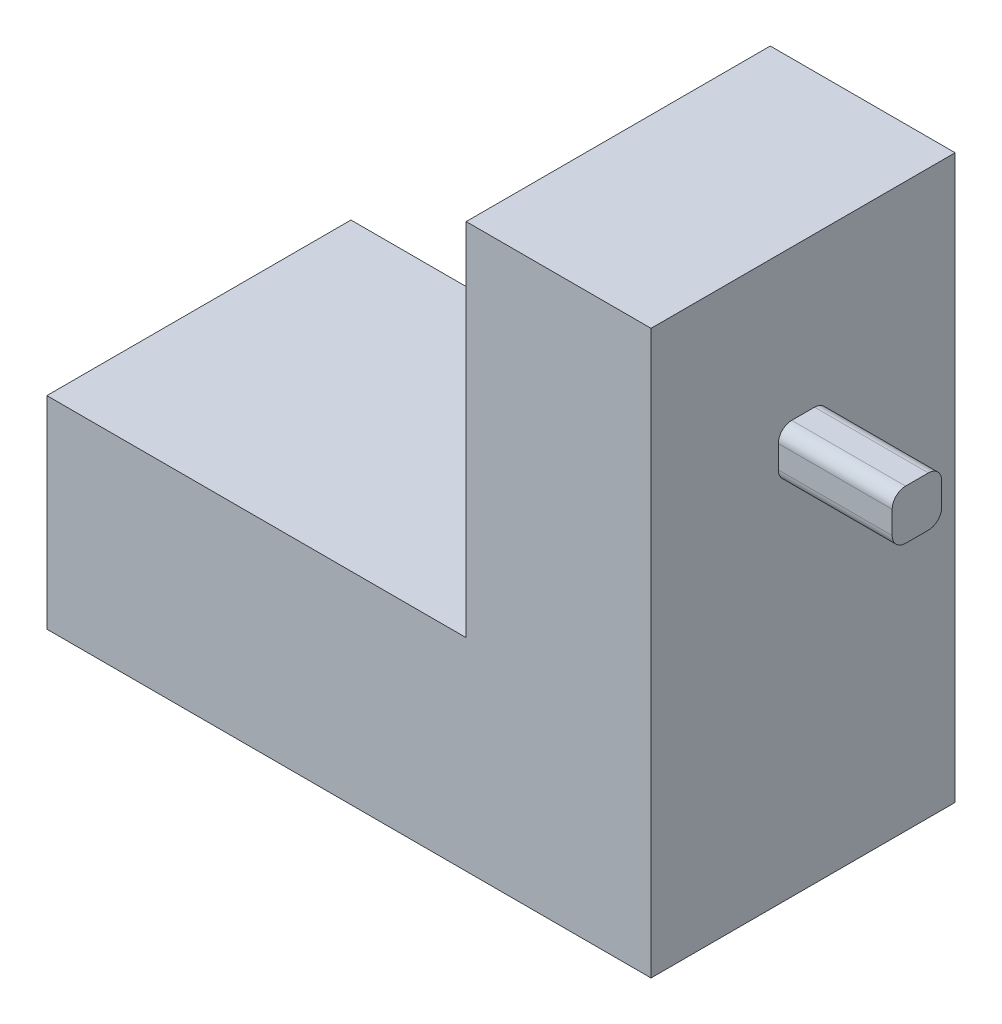
SolidWorks part; units mm, degrees
ref_plane "Plano frontal" through (0, 0, 0) normal (0, 0, 1) x (1, 0, 0)
ref_plane "Plano superior" through (0, 0, 0) normal (0, 1, 0) x (1, 0, 0)
ref_plane "Plano direito" through (0, 0, 0) normal (1, 0, 0) x (0, 0, -1)
sketch "Esboço1" plane through (0, 0, 0) normal (0, 0, 1) x (1, 0, 0)
  line L0 (-52.044, 13.5553) -> (-52.044, -1.5447)
  line L1 (-52.044, -1.5447) -> (-6.944, -1.5447)
  line L2 (-6.944, -1.5447) -> (-6.944, 25.5553)
  line L3 (-6.944, 25.5553) -> (1.556, 25.5553)
  line L4 (1.556, 25.5553) -> (1.556, 29.2553)
  line L5 (1.556, 29.2553) -> (-6.944, 29.2553)
  line L6 (-6.944, 29.2553) -> (-6.944, 40.4553)
  line L7 (-6.944, 40.4553) -> (-20.744, 40.4553)
  line L8 (-20.744, 40.4553) -> (-20.744, 13.5553)
  line L9 (-20.744, 13.5553) -> (-52.044, 13.5553)
  dimension "D1" = 27.1
  dimension "D2" = 3.7
  dimension "D3" = 11.2
  dimension "D4" = 8.5
  dimension "D5" = 45.1
  dimension "D6" = 13.8
  dimension "D7" = 15.1
extrude "Ressalto-extrusão1" add sketch "Esboço1" along normal blind 22.7
sketch "Esboço2" plane through (0, 0, 22.7) normal (0, 0, 1) x (1, 0, 0)
  line L0 (-6.944, 25.5553) -> (1.556, 25.5553) construction
  line L1 (-6.944, 29.2553) -> (1.556, 29.2553)
  line L2 (-6.944, 29.2553) -> (-6.944, 25.5553)
  line L3 (-6.944, 25.5553) -> (1.556, 25.5553)
  line L4 (1.556, 29.2553) -> (1.556, 25.5553)
extrude "Corte-extrusão1" cut sketch "Esboço2" against normal blind 9.5
sketch "Esboço3" plane through (0, 0, 0) normal (0, 0, -1) x (-1, 0, 0)
  line L1 (6.944, 29.2553) -> (-1.5839, 29.2553)
  line L2 (6.944, 29.2553) -> (6.944, 25.1964)
  line L3 (6.944, 25.1964) -> (-1.5839, 25.1964)
  line L4 (-1.5839, 29.2553) -> (-1.5839, 25.1964)
extrude "Corte-extrusão2" cut sketch "Esboço3" against normal blind 9.5
fillet "Filete4" radius 1 4 edges at (-2.694, 29.2553, 9.5) (-2.694, 25.5553, 9.5) (-2.694, 25.5553, 13.2) (-2.694, 29.2553, 13.2)
